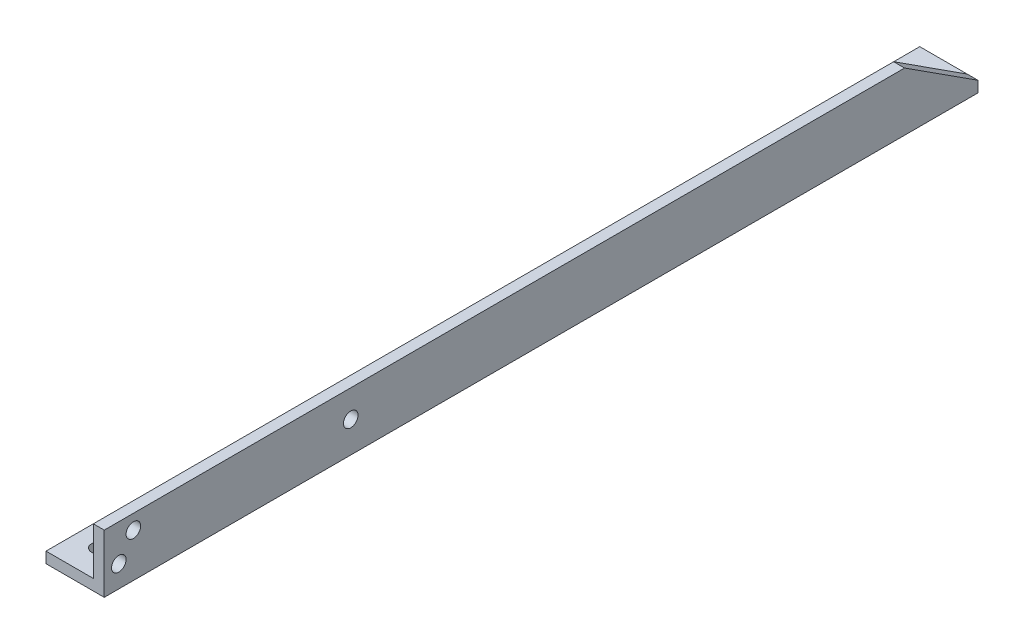
SolidWorks part; units mm, degrees
material "6061 Alloy"
ref_plane "Front Plane" through (0, 0, 0) normal (0, 0, 1) x (1, 0, 0)
ref_plane "Top Plane" through (0, 0, 0) normal (0, 1, 0) x (1, 0, 0)
ref_plane "Right Plane" through (0, 0, 0) normal (1, 0, 0) x (0, 0, -1)
sketch "Sketch1" plane through (0, 0, 0) normal (0, 0, 1) x (1, 0, 0)
  line L0 (0, 0) -> (0, -25.4)
  line L1 (0, -25.4) -> (-25.4, -25.4)
  line L2 (-25.4, -25.4) -> (-25.4, -20.6375)
  line L3 (-25.4, -20.6375) -> (-4.7625, -20.6375)
  line L4 (-4.7625, -20.6375) -> (-4.7625, 0)
  line L5 (-4.7625, 0) -> (0, 0)
  dimension "D1" = 4.7625
  dimension "D2" = 4.7625
  dimension "D3" = 25.4
  dimension "D4" = 25.4
extrude "Boss-Extrude1" add sketch "Sketch1" along normal blind 381
sketch "Sketch9" plane through (-4.7625, 0, 0) normal (-1, 0, 0) x (0, 0, 1)
  line L0 (0, -20.6375) -> (32.0266, 0)
  line L1 (381, 0) -> (0, 0) construction
  dimension "D1" = 38.1
extrude "Cut-Extrude2" cut sketch "Sketch9" against normal through all and the other way through all
sketch "Sketch10" plane through (-4.7625, 0, 0) normal (-1, 0, 0) x (0, 0, 1)
  line L0 (381, 0) -> (32.0266, 0) construction
  line L1 (381, 0) -> (381, -20.6375) construction
  circle A0 centre (374.65, -15.875) radius 3.175
  circle A1 centre (368.3, -6.35) radius 3.175
  dimension "D1" = 6.35
  dimension "D2" = 6.35
  dimension "D3" = 15.875
  dimension "D4" = 6.35
  dimension "D5" = 6.35
  dimension "D6" = 12.7
extrude "Cut-Extrude3" cut sketch "Sketch10" against normal up to next
sketch "Sketch11" plane through (0, 0, 0) normal (1, 0, 0) x (0, 0, -1)
  circle A0 centre (-273.5093, -11.9296) radius 3.175 construction
  circle A1 centre (-273.5093, -11.9296) radius 3.175
extrude "Cut-Extrude4" cut sketch "Sketch11" against normal up to next
sketch "Sketch12" plane through (0, -20.6375, 0) normal (0, 1, 0) x (1, 0, 0)
  line L0 (-25.4, -381) -> (-25.4, 0) construction
  line L1 (-4.7625, -381) -> (-25.4, -381) construction
  circle A0 centre (-15.0812, -368.3) radius 3.175
  dimension "D1" = 6.35
  dimension "D2" = 10.3187
  dimension "D3" = 12.7
extrude "Cut-Extrude5" cut sketch "Sketch12" against normal up to next
